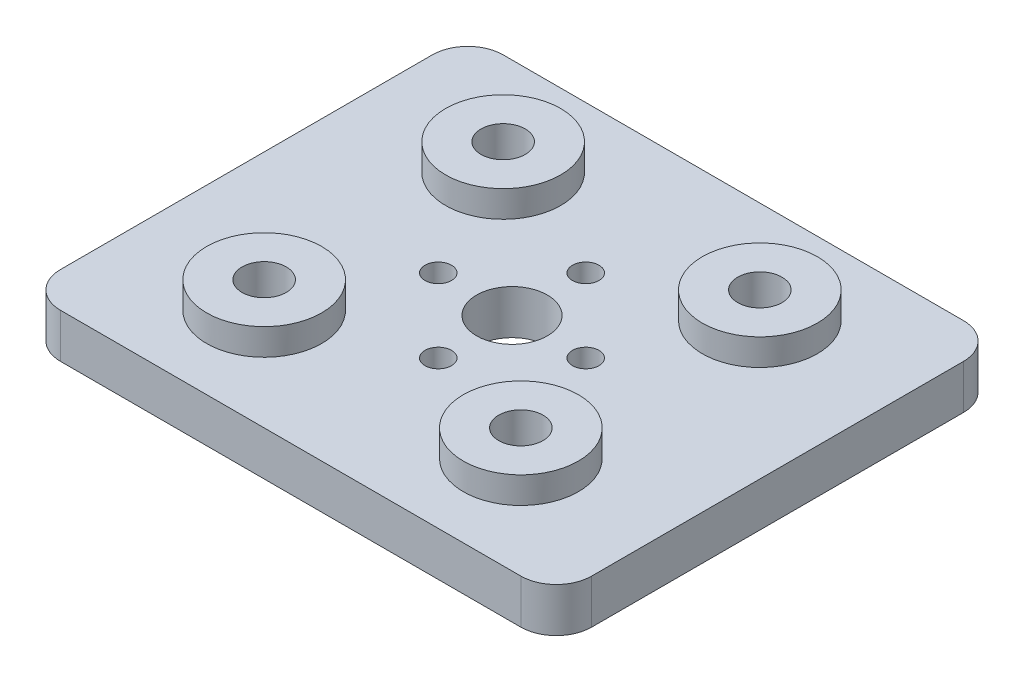
SolidWorks part; units mm, degrees
ref_plane "Front Plane" through (0, 0, 0) normal (0, 0, 1) x (1, 0, 0)
ref_plane "Top Plane" through (0, 0, 0) normal (0, 1, 0) x (1, 0, 0)
ref_plane "Right Plane" through (0, 0, 0) normal (1, 0, 0) x (0, 0, -1)
sketch "Sketch3" plane through (0, 0, 0) normal (0, 1, 0) x (1, 0, 0)
  line L1 (-10.7319, -22.2022) -> (49.2681, -22.2022)
  line L2 (-10.7319, -22.2022) -> (-10.7319, 27.7978)
  line L3 (-10.7319, 27.7978) -> (49.2681, 27.7978)
  line L4 (49.2681, -22.2022) -> (49.2681, 27.7978)
  circle A0 centre (19.2681, 2.7978) radius 4
  circle A1 centre (10.9381, 2.7978) radius 1.5
  circle A2 centre (19.2681, 11.1278) radius 1.5
  circle A3 centre (27.5981, 2.7978) radius 1.5
  circle A4 centre (19.2681, -5.5322) radius 1.5
  point P17 (9.2681, 2.7978)
  point P18 (19.2681, 2.7978)
  dimension "D3" = 8
  dimension "D4" = 3
  dimension "D5" = 8.33
  dimension "D6" = 30
  dimension "D7" = 25
  dimension "D1" = 60
  dimension "D2" = 50
extrude "Boss-Extrude1" add sketch "Sketch3" along normal blind 5
sketch "Sketch4" plane through (0, 5, 0) normal (0, 1, 0) x (1, 0, 0)
  circle A0 centre (4.7681, 16.2978) radius 2.5
  circle A1 centre (33.7681, 16.2978) radius 2.5
  circle A2 centre (33.7681, -10.7022) radius 2.5
  circle A3 centre (4.7681, -10.7022) radius 2.5
  circle A4 centre (19.2681, 2.7978) radius 4 construction
  dimension "D1" = 5
  dimension "D4" = 14.5
  dimension "D5" = 27
  dimension "D6" = 13.5
  dimension "D7" = 29
  dimension "D2" = 2
  dimension "D3" = 2
extrude "Cut-Extrude1" cut sketch "Sketch4" against normal blind 5
fillet "Fillet1" radius 4 4 edges at (-10.7319, 2.5, 22.2022) (49.2681, 2.5, 22.2022) (49.2681, 2.5, -27.7978) (-10.7319, 2.5, -27.7978)
sketch "Sketch5" plane through (0, 5, 0) normal (0, 1, 0) x (1, 0, 0)
  circle A0 centre (33.7681, 16.2978) radius 6.5
  circle A1 centre (33.7681, 16.2978) radius 2.5
  dimension "D1" = 4
extrude "Boss-Extrude2" add sketch "Sketch5" along normal blind 3
pattern_linear "LPattern1" count 2 spacing 29 along (-1, 0, 0) count 2 spacing 27 along (0, 0, 1) of "Boss-Extrude2"
